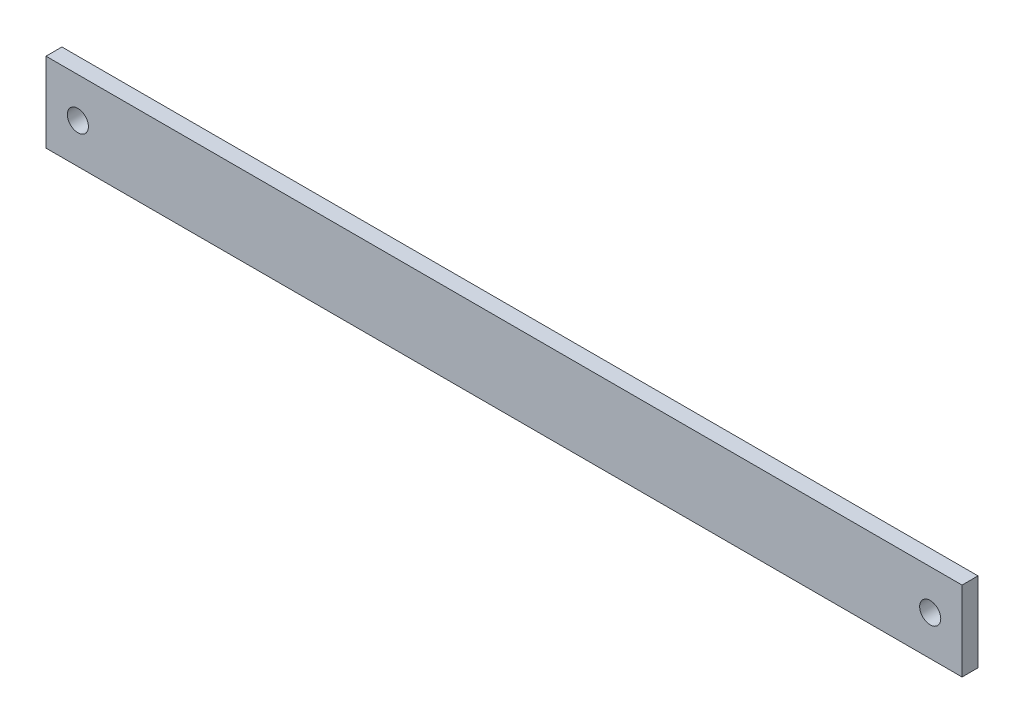
SolidWorks part; units mm, degrees
ref_plane "Front Plane" through (0, 0, 0) normal (0, 0, 1) x (1, 0, 0)
ref_plane "Top Plane" through (0, 0, 0) normal (0, 1, 0) x (1, 0, 0)
ref_plane "Right Plane" through (0, 0, 0) normal (1, 0, 0) x (0, 0, -1)
sketch "Extrusion Base Sketch" plane through (0, 0, 0) normal (0, 0, 1) x (1, 0, 0)
  line L0 (230, 20) -> (230, 0)
  line L1 (21.25, 2.5) -> (208.75, 2.5) construction
  line L2 (21.25, 2.5) -> (21.25, 17.5) construction
  line L3 (21.25, 17.5) -> (208.75, 17.5) construction
  line L4 (208.75, 2.5) -> (208.75, 17.5) construction
  line L5 (0, 20) -> (230, 20)
  line L6 (18.75, 20) -> (18.75, 0) construction
  line L7 (0, 0) -> (230, 0)
  line L8 (211.25, 20) -> (211.25, 0) construction
  line L9 (0, 20) -> (0, 0)
  line L11 (222, 10) -> (230, 10) construction
  circle A0 centre (8, 10) radius 2.65
  circle A2 centre (222, 10) radius 2.65
  dimension "D8" = 5.3
  dimension "D1" = 15
  dimension "D2" = 187.5
  dimension "D4" = 2.5
  dimension "D5" = 2.5
  dimension "D6" = 2.5
  dimension "D3" = 20
  dimension "D7" = 21.25
extrude "Extrusion Base Extrude" add sketch "Extrusion Base Sketch" against normal blind 4
equation "\"Logo Height\"= 15mm"
equation "\"Total Height\"= 20mm"
equation "\"Border\"= ( \"Total Height\" - \"Logo Height\" ) / 2"
equation "\"Text Length\"= 187.5mm"
equation "\"D1@Extrusion Base Sketch\" = \"Logo Height\""
equation "\"D2@Extrusion Base Sketch\" = \"Text Length\""
equation "\"D4@Extrusion Base Sketch\" = \"Border\""
equation "\"D5@Extrusion Base Sketch\" = \"Border\""
equation "\"D6@Extrusion Base Sketch\" = \"Border\""
equation "\"D3@Extrusion Base Sketch\" = \"Total Height\""
